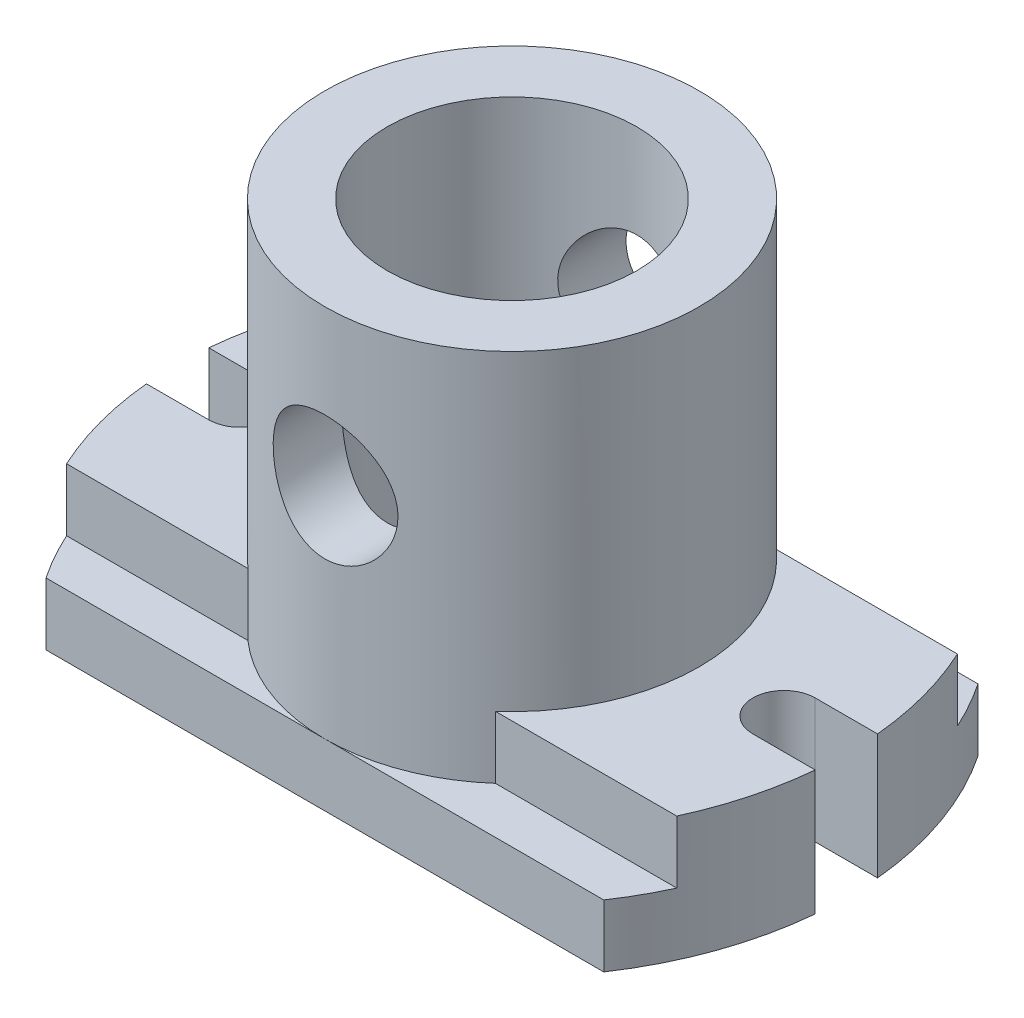
SolidWorks part; units mm, degrees
ref_plane "前视基准面" through (0, 0, 0) normal (0, 0, 1) x (1, 0, 0)
ref_plane "上视基准面" through (0, 0, 0) normal (0, 1, 0) x (1, 0, 0)
ref_plane "右视基准面" through (0, 0, 0) normal (1, 0, 0) x (0, 0, -1)
other "Configuration Table"
sketch "草图2" plane through (0, 0, 0) normal (0, 1, 0) x (1, 0, 0)
  line L0 (53.6094, 5) -> (43.6094, 5)
  line L1 (53.6094, -5) -> (43.6094, -5)
  line L2 (-53.6094, 5) -> (-43.6094, 5)
  line L3 (-77.9421, 0) -> (129.075, 0) construction
  line L4 (0, 75.6051) -> (0, -88.2991) construction
  line L5 (-53.6094, -5) -> (-43.6094, -5)
  line L6 (44.7099, 30) -> (-44.7099, 30)
  line L7 (-44.7099, -30) -> (44.7099, -30)
  arc A0 (53.6094, 5) -> (44.7099, 30) centre (0, 0) ccw
  arc A3 (-53.6094, -5) -> (-44.7099, -30) centre (0, 0) ccw
  arc A4 (-44.7099, 30) -> (-53.6094, 5) centre (0, 0) ccw
  arc A5 (44.7099, -30) -> (53.6094, -5) centre (0, 0) ccw
  arc A6 (-43.6094, -5) -> (-43.6094, 5) centre (-43.6094, 0) ccw
  arc A7 (43.6094, 5) -> (43.6094, -5) centre (43.6094, 0) ccw
  dimension "D1" = 5
  dimension "D2" = 5
  dimension "D3" = 10
  dimension "D4" = 10
  dimension "D5" = 10
  dimension "D6" = 10
  dimension "D7" = 30
  dimension "D8" = 30
extrude "凸台-拉伸1" add sketch "草图2" along normal blind 10
sketch "草图3" plane through (0, 10, 0) normal (0, 1, 0) x (1, 0, 0)
  circle A0 centre (0, 0) radius 30
  dimension "D1" = 60
extrude "凸台-拉伸2" add sketch "草图3" along normal blind 60
sketch "草图4" plane through (0, 0, 0) normal (0, 0, 1) x (1, 0, 0)
  line L0 (38.451, 45) -> (-40.0129, 45) construction
  line L1 (-44.7099, 0) -> (44.7099, 0) construction
  circle A0 centre (0, 45) radius 10
  dimension "D1" = 20
  dimension "D2" = 45
extrude "切除-拉伸1" cut sketch "草图4" against normal through all both and the other way through all
sketch "草图7" plane through (0, 10, 0) normal (0, 1, 0) x (1, 0, 0)
  line L0 (-48.9155, -22.5) -> (-19.8431, -22.5)
  line L1 (-48.9155, 22.5) -> (-19.8431, 22.5)
  line L2 (-52.0614, 0) -> (68.4235, 0) construction
  line L3 (19.8431, -22.5) -> (48.9155, -22.5)
  line L4 (19.8431, 22.5) -> (48.9155, 22.5)
  line L5 (-53.6094, 5) -> (-43.6094, 5)
  line L6 (-53.6094, -5) -> (-43.6094, -5)
  line L7 (53.6094, 5) -> (43.6094, 5)
  line L8 (53.6094, -5) -> (43.6094, -5)
  arc A0 (-53.6094, -5) -> (-44.7099, -30) centre (0, 0) ccw construction
  arc A1 (44.7099, -30) -> (53.6094, -5) centre (0, 0) ccw construction
  arc A2 (-19.8431, 22.5) -> (-19.8431, -22.5) centre (0, 0) ccw
  arc A3 (-44.7099, 30) -> (-53.6094, 5) centre (0, 0) ccw construction
  arc A4 (53.6094, 5) -> (44.7099, 30) centre (0, 0) ccw construction
  arc A5 (48.9155, -22.5) -> (53.6094, -5) centre (0, 0) ccw
  arc A6 (-48.9155, 22.5) -> (-53.6094, 5) centre (0, 0) ccw
  arc A7 (19.8431, -22.5) -> (19.8431, 22.5) centre (0, 0) ccw
  arc A8 (-43.6094, -5) -> (-43.6094, 5) centre (-43.6094, 0) ccw
  arc A9 (-53.6094, -5) -> (-48.9155, -22.5) centre (0, 0) ccw
  arc A10 (43.6094, 5) -> (43.6094, -5) centre (43.6094, 0) ccw
  arc A11 (53.6094, 5) -> (48.9155, 22.5) centre (0, 0) ccw
  dimension "D1" = 22.5
  dimension "D2" = 22.5
extrude "凸台-拉伸3" add sketch "草图7" along normal blind 10
sketch "草图8" plane through (0, 70, 0) normal (0, 1, 0) x (1, 0, 0)
  circle A0 centre (0, 0) radius 20
  dimension "D1" = 40
extrude "切除-拉伸2" cut sketch "草图8" against normal through all both
sketch "草图11" plane through (0, 20, 0) normal (0, 1, 0) x (1, 0, 0)
  line L0 (29.5804, 5) -> (34.5804, 5)
  line L1 (34.5804, 5) -> (34.5804, -5)
  line L2 (34.5804, -5) -> (29.5804, -5)
  line L3 (-29.5804, 5) -> (-34.5804, 5)
  line L4 (-34.5804, 5) -> (-34.5804, -5)
  line L5 (-34.5804, -5) -> (-29.5804, -5)
  arc A0 (-29.5804, 5) -> (-29.5804, -5) centre (0, 0) ccw
  arc A1 (29.5804, -5) -> (29.5804, 5) centre (0, 0) ccw
  dimension "D1" = 5
  dimension "D2" = 5
ref_plane "基准面1" through (0, 40, 0) normal (0, 1, 0) x (1, 0, 0)
sketch "草图12" plane through (0, 40, 0) normal (0, 1, 0) x (1, 0, 0)
  arc A0 (29.5804, -5) -> (29.5804, 5) centre (0, 0) ccw
  arc A1 (-29.5804, 5) -> (-29.5804, -5) centre (0, 0) ccw
